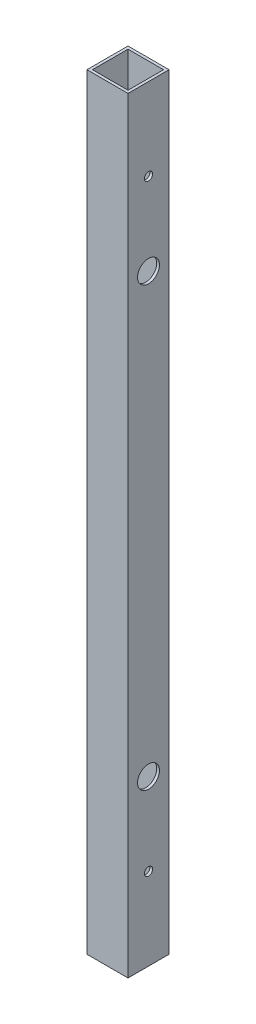
SolidWorks part; units mm, degrees
ref_plane "前视基准面" through (0, 0, 0) normal (0, 0, 1) x (1, 0, 0)
ref_plane "上视基准面" through (0, 0, 0) normal (0, 1, 0) x (1, 0, 0)
ref_plane "右视基准面" through (0, 0, 0) normal (1, 0, 0) x (0, 0, -1)
sketch "草图1" plane through (0, 0, 0) normal (0, 1, 0) x (1, 0, 0)
  line L0 (-6.5, 6.5) -> (6.5, 6.5)
  line L1 (-7.5, -7.5) -> (7.5, -7.5)
  line L2 (-7.5, -7.5) -> (-7.5, 7.5)
  line L3 (-7.5, 7.5) -> (7.5, 7.5)
  line L4 (7.5, -7.5) -> (7.5, 7.5)
  line L5 (-7.5, -7.5) -> (7.5, 7.5) construction
  line L6 (-7.5, 7.5) -> (7.5, -7.5) construction
  line L7 (6.5, -6.5) -> (6.5, 6.5)
  line L8 (-6.5, -6.5) -> (6.5, -6.5)
  line L9 (-6.5, -6.5) -> (-6.5, 6.5)
  point P0 (0, 0)
  dimension "D1" = 15
  dimension "D2" = 15
  dimension "D3" = 1
extrude "凸台-拉伸1" add sketch "草图1" along normal blind 280
sketch "草图2" plane through (-7.5, 0, 0) normal (-1, 0, 0) x (0, 0, 1)
  line L0 (-7.5, 280) -> (7.5, 280) construction
  line L1 (65.5708, 140) -> (-113.1166, 140) construction
  circle A0 centre (0, 220) radius 1.5
  circle A1 centre (0, 60) radius 1.5
  dimension "D1" = 60
extrude "切除-拉伸1" cut sketch "草图2" against normal blind 260
sketch "草图3" plane through (7.5, 0, 0) normal (1, 0, 0) x (0, 0, -1)
  circle A0 centre (0, 60) radius 4
  circle A1 centre (0, 220) radius 4
extrude "切除-拉伸2" cut sketch "草图3" against normal blind 2
sketch "草图4" plane through (7.5, 0, 0) normal (1, 0, 0) x (0, 0, -1)
  line L0 (-7.5, 280) -> (7.5, 280) construction
  line L1 (13.7591, 140) -> (-26.513, 140) construction
  circle A0 centre (0, 250) radius 1.5
  circle A1 centre (0, 30) radius 1.5
  dimension "D1" = 30
extrude "切除-拉伸3" cut sketch "草图4" against normal through all
sketch "草图5" plane through (-7.5, 0, 0) normal (-1, 0, 0) x (0, 0, 1)
  circle A0 centre (0, 250) radius 4
  circle A1 centre (0, 30) radius 4
extrude "切除-拉伸4" cut sketch "草图5" against normal blind 2
